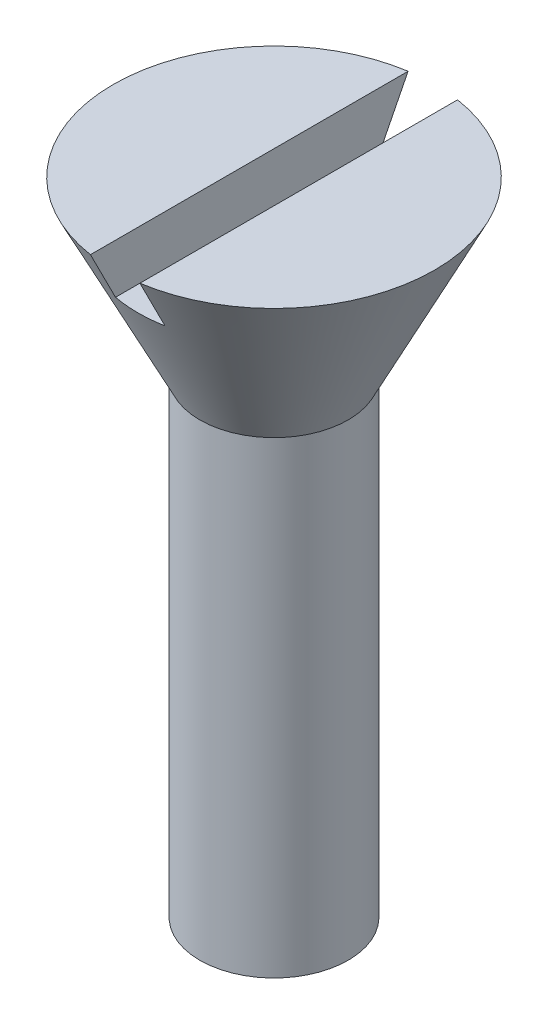
SolidWorks part; units mm, degrees
ref_plane "Front Plane" through (0, 0, 0) normal (0, 0, 1) x (1, 0, 0)
ref_plane "Top Plane" through (0, 0, 0) normal (0, 1, 0) x (1, 0, 0)
ref_plane "Right Plane" through (0, 0, 0) normal (1, 0, 0) x (0, 0, -1)
sketch "Sketch1" plane through (0, 0, 0) normal (0, 0, 1) x (1, 0, 0)
  line L0 (0, 0) -> (0, 50000) construction
  line L1 (0, 0) -> (0, -18.9241)
  line L2 (0, -18.9241) -> (-3, -18.9241)
  line L3 (-3, -18.9241) -> (-3, 0)
  line L4 (0, 5) -> (-1, 5)
  line L5 (-1, 5) -> (-1, 7)
  line L6 (-1, 7) -> (-6.5, 7)
  line L7 (-6.5, 7) -> (-3, 0)
  line L8 (0, 5) -> (0, 0)
  point P0 (0, 0)
  point P20 (0, -10.6537)
  dimension "D1" = 18.9241
  dimension "D2" = 3
  dimension "D3" = 2
  dimension "D4" = 1
  dimension "D5" = 5
  dimension "D6" = 5.5
  dimension "D7" = 7
revolve "Revolve3" add sketch "Sketch1" angle 360 about L8
sketch "Sketch2" plane through (0, 0, 0) normal (0, 0, 1) x (1, 0, 0)
  line L0 (-3, -18.9241) -> (0, -20.6562)
  line L2 (0, -200000) -> (0, 250000) construction
  line L3 (-3, -18.9241) -> (0, -18.9241)
  line L4 (0, -18.9241) -> (0, -20.6562)
  point P6 (0, -20.6562)
  dimension "D1" = 1.7321
revolve "Revolve4" add sketch "Sketch2" angle 360 about L4
sketch "Sketch3" plane through (0, 0, 0) normal (0, 0, 1) x (1, 0, 0)
  line L0 (-1, 7) -> (-1, 5)
  line L1 (-1, 5) -> (1, 5)
  line L4 (1, 7) -> (-1, 7)
  line L5 (1, 7) -> (1, 5)
  dimension "D1" = 2
  dimension "D2" = 1
extrude "Cut-Extrude1" cut sketch "Sketch3" against normal through all both and the other way through all
